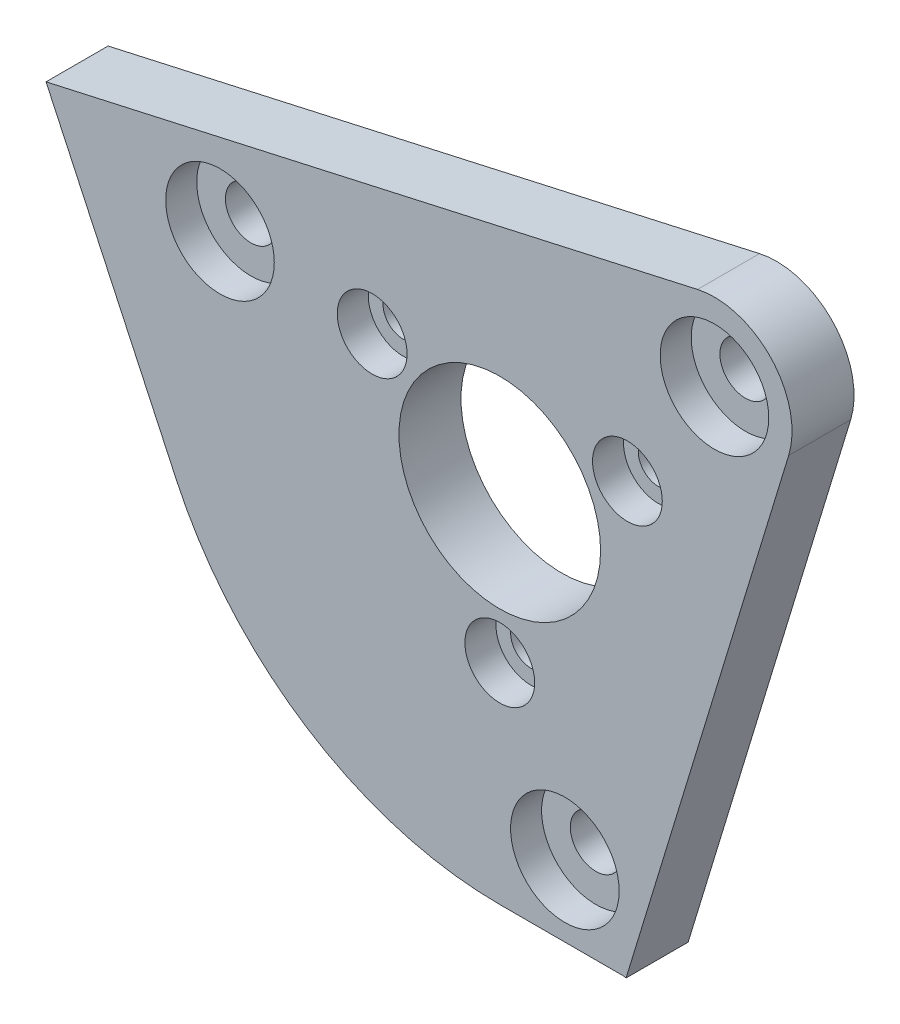
SolidWorks part; units mm, degrees
material "Thornel Mat VMA"
ref_plane "前视基准面" through (0, 0, 0) normal (0, 0, 1) x (1, 0, 0)
ref_plane "上视基准面" through (0, 0, 0) normal (0, 1, 0) x (1, 0, 0)
ref_plane "右视基准面" through (0, 0, 0) normal (1, 0, 0) x (0, 0, -1)
sketch "草图1" plane through (0, 0, 0) normal (0, 0, 1) x (1, 0, 0)
  line L0 (8.5535, -18.0718) -> (16.5535, -18.0718)
  line L1 (16.5535, -18.0718) -> (22.4243, 1.2034)
  line L2 (5.3837, 19.5775) -> (-21.1971, 13.6228)
  line L3 (-21.1971, 13.6228) -> (-12.7448, -4.5034)
  arc A0 (-12.7448, -4.5034) -> (8.5535, -18.0718) centre (8.5535, 5.4282) ccw
  arc A1 (22.4243, 1.2034) -> (5.3837, 19.5775) centre (8.5535, 5.4282) ccw
  circle A2 centre (16.7807, 10.1782) radius 1.3
  circle A3 centre (8.5535, -4.0718) radius 1.3
  circle A4 centre (8.5535, 5.4282) radius 6.5
  circle A5 centre (0.3262, 10.1782) radius 1.3
extrude "凸台-拉伸1" add sketch "草图1" along normal blind 4
sketch "草图2" plane through (0, 0, 4) normal (0, 0, 1) x (1, 0, 0)
  line L4 (-20.744, 13.8341) -> (-26.7918, 13.8341)
  line L5 (-26.7918, 13.8341) -> (-7.8105, -16.6788)
  line L6 (8.5535, -17.5718) -> (16.5535, -17.5718)
  line L7 (-20.744, 13.8341) -> (-12.2916, -4.2921)
  line L8 (8.5535, -17.5718) -> (16.5535, -17.5718)
  line L9 (-20.744, 13.8341) -> (-12.2916, -4.2921)
  line L10 (-7.8105, -16.6788) -> (17.2904, -20.5165)
  line L11 (17.2904, -20.5165) -> (21.4055, -18.5977)
  line L12 (21.4055, -18.5977) -> (16.5535, -17.5718)
  arc A3 (-12.2916, -4.2921) -> (8.5535, -17.5718) centre (8.5535, 5.4282) ccw
  arc A4 (-12.2916, -4.2921) -> (8.5535, -17.5718) centre (8.5535, 5.4282) ccw
  dimension "D1" = 0.5
extrude "切除-拉伸1" cut sketch "草图2" against normal blind 2 contours L4 L5 L10 L11 L12 L8 A4 L9
sketch "草图3" plane through (0, 0, 4) normal (0, 0, 1) x (1, 0, 0)
  line L7 (16.5535, -18.0718) -> (16.6965, -17.6021)
  line L8 (16.6965, -17.6021) -> (16.5535, -17.5718)
  line L9 (16.5535, -17.5718) -> (8.5535, -17.5718)
  line L10 (-12.2916, -4.2921) -> (-20.6976, 13.7347)
  line L11 (-20.6976, 13.7347) -> (-21.1971, 13.6228)
  line L12 (-21.1971, 13.6228) -> (-12.7448, -4.5034)
  line L13 (8.5535, -18.0718) -> (16.5535, -18.0718)
  line L14 (16.5535, -18.0718) -> (16.6965, -17.6021)
  line L15 (16.6965, -17.6021) -> (16.5535, -17.5718)
  line L16 (16.5535, -17.5718) -> (8.5535, -17.5718)
  line L17 (-12.2916, -4.2921) -> (-20.6976, 13.7347)
  line L18 (-20.6976, 13.7347) -> (-21.1971, 13.6228)
  line L19 (-21.1971, 13.6228) -> (-12.7448, -4.5034)
  line L20 (8.5535, -18.0718) -> (16.5535, -18.0718)
  arc A2 (-12.2916, -4.2921) -> (8.5535, -17.5718) centre (8.5535, 5.4282) ccw
  arc A3 (-12.7448, -4.5034) -> (8.5535, -18.0718) centre (8.5535, 5.4282) ccw
  arc A4 (-12.2916, -4.2921) -> (8.5535, -17.5718) centre (8.5535, 5.4282) ccw
  arc A5 (-12.7448, -4.5034) -> (8.5535, -18.0718) centre (8.5535, 5.4282) ccw
  dimension "D1" = 0
extrude "切除-拉伸2" cut sketch "草图3" against normal blind 10
sketch "草图4" plane through (0, 0, 4) normal (0, 0, 1) x (1, 0, 0)
  line L0 (5.3837, 19.5775) -> (29.6784, 25.02)
  line L1 (22.4243, 1.2034) -> (29.6784, 25.02)
  line L2 (16.6965, -17.6021) -> (22.4243, 1.2034) construction
  line L3 (5.3837, 19.5775) -> (-20.6976, 13.7347) construction
  arc A0 (22.4243, 1.2034) -> (5.3837, 19.5775) centre (8.5535, 5.4282) ccw construction
  arc A1 (22.4243, 1.2034) -> (5.3837, 19.5775) centre (8.5535, 5.4282) ccw
extrude "凸台-拉伸2" add sketch "草图4" against normal up to surface (4 mm away) up to face at (5.7097, -2.9518, 0)
fillet "圆角1" radius 5 1 edges at (29.6784, 25.02, 2)
sketch "草图5" plane through (0, 0, 4) normal (0, 0, 1) x (1, 0, 0)
  line L1 (22.394, 18.2642) -> (-9.4831, 10.9964) construction
  line L2 (-9.4831, 10.9964) -> (12.7495, -12.9761) construction
  line L3 (12.7495, -12.9761) -> (22.394, 18.2642) construction
  circle A0 centre (22.394, 18.2642) radius 1.65
  circle A1 centre (8.5535, 5.4282) radius 9.4383 construction
  circle A2 centre (-9.4831, 10.9964) radius 1.65
  circle A3 centre (12.7495, -12.9761) radius 1.65
  dimension "D1" = 3.3
  dimension "D2" = 3.3
  dimension "D3" = 3.3
extrude "切除-拉伸3" cut sketch "草图5" against normal blind 10
sketch "草图6" plane through (0, 0, 4) normal (0, 0, 1) x (1, 0, 0)
  circle A0 centre (22.394, 18.2642) radius 3.5
  circle A1 centre (-9.4831, 10.9964) radius 3.5
  circle A2 centre (12.7495, -12.9761) radius 3.5
  circle A3 centre (8.5535, -4.0718) radius 2.25
  circle A4 centre (16.7807, 10.1782) radius 2.25
  circle A5 centre (0.3262, 10.1782) radius 2.25
  dimension "D1" = 7
  dimension "D2" = 7
  dimension "D3" = 7
  dimension "D4" = 4.5
  dimension "D5" = 4.5
  dimension "D6" = 4.5
extrude "切除-拉伸4" cut sketch "草图6" against normal blind 2
